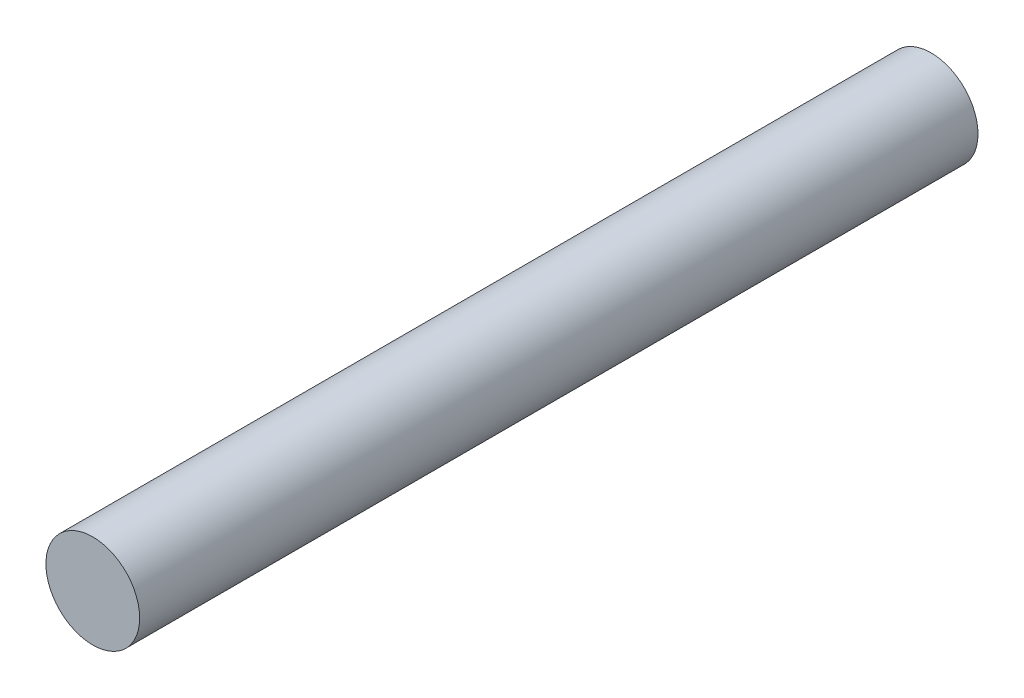
SolidWorks part; units mm, degrees
ref_plane "Front Plane" through (0, 0, 0) normal (0, 0, 1) x (1, 0, 0)
ref_plane "Top Plane" through (0, 0, 0) normal (0, 1, 0) x (1, 0, 0)
ref_plane "Right Plane" through (0, 0, 0) normal (1, 0, 0) x (0, 0, -1)
sketch "Sketch1" plane through (0, 0, 0) normal (0, 0, 1) x (1, 0, 0)
  circle A0 centre (0, 0) radius 9.017
extrude "Boss-Extrude1" add sketch "Sketch1" along normal blind 161.29 contours A0
